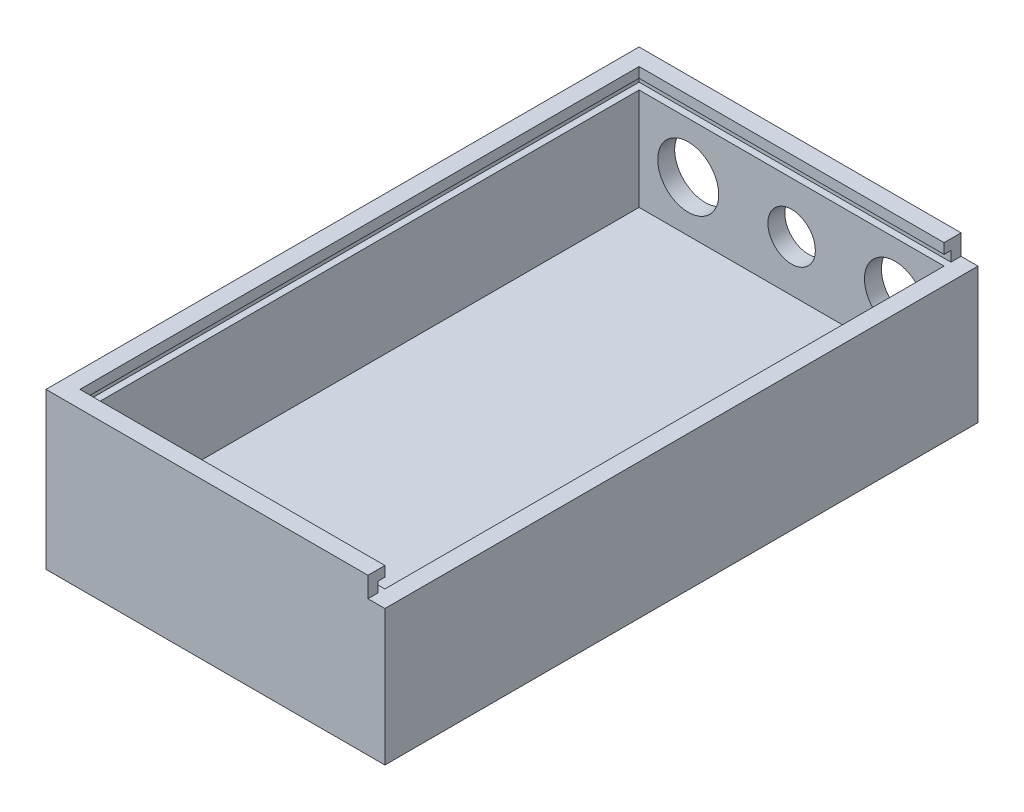
SolidWorks part; units mm, degrees
ref_plane "Front Plane" through (0, 0, 0) normal (0, 0, 1) x (1, 0, 0)
ref_plane "Top Plane" through (0, 0, 0) normal (0, 1, 0) x (1, 0, 0)
ref_plane "Right Plane" through (0, 0, 0) normal (1, 0, 0) x (0, 0, -1)
sketch "Sketch1" plane through (0, 0, 0) normal (0, 0, 1) x (1, 0, 0)
  line L0 (6.2525, 13.33) -> (6.2525, -26.67) construction
  line L1 (-43.7475, 13.33) -> (56.2525, 13.33)
  line L2 (-43.7475, 13.33) -> (-43.7475, -26.67)
  line L3 (-43.7475, -26.67) -> (56.2525, -26.67)
  line L4 (56.2525, 13.33) -> (56.2525, -26.67)
  line L5 (-43.7475, -6.67) -> (56.2525, -6.67) construction
  line L6 (6.2525, -6.67) -> (36.7525, -6.67)
  line L7 (6.2525, -6.67) -> (-24.2475, -6.67)
  circle A0 centre (6.2525, -6.67) radius 6.5
  circle A1 centre (36.7525, -6.67) radius 9
  circle A2 centre (-24.2475, -6.67) radius 9
  dimension "D3" = 13
  dimension "D5" = 18
  dimension "D7" = 18
  dimension "D1" = 100
  dimension "D2" = 40
  dimension "D4" = 30.5
  dimension "D6" = 30.5
extrude "Boss-Extrude1" add sketch "Sketch1" along normal blind 175 contours L2 L1 L4 L3
sketch "Sketch2" plane through (0, 13.33, 0) normal (0, 1, 0) x (1, 0, 0)
  line L0 (6.2525, 0) -> (6.2525, -175) construction
  line L2 (56.2525, -87.5) -> (-43.7475, -87.5) construction
  line L3 (56.2525, -175) -> (56.2525, 0) construction
  line L4 (-43.7475, -175) -> (-43.7475, 0) construction
  line L5 (-43.7475, 0) -> (56.2525, 0) construction
  line L10 (-43.7475, -175) -> (56.2525, -175) construction
  line L11 (-38.7475, -170) -> (51.2525, -170)
  line L12 (-38.7475, -170) -> (-38.7475, -5)
  line L13 (-38.7475, -5) -> (51.2525, -5)
  line L14 (51.2525, -170) -> (51.2525, -5)
  line L15 (-38.7475, -170) -> (51.2525, -5) construction
  line L16 (-38.7475, -5) -> (51.2525, -170) construction
  point P4 (6.2525, -87.5)
  dimension "D2" = 90
  dimension "D3" = 165
extrude "Cut-Extrude1" cut sketch "Sketch2" against normal blind 30 contours L12 L11 L14 L13
ref_plane "Plane1" through (0, 13.33, 0) normal (0, 1, 0) x (1, 0, 0)
ref_plane "Plane10" through (0, -16.67, 0) normal (0, 1, 0) x (1, 0, 0)
sketch "Sketch18" plane through (0, 0, 0) normal (0, 0, 1) x (1, 0, 0)
  line L0 (56.2525, 13.33) -> (56.2525, -26.67) construction
  line L1 (-43.7475, 13.33) -> (-43.7475, -26.67) construction
  line L2 (-43.7475, 13.33) -> (56.2525, 13.33) construction
  circle A0 centre (6.2525, -1.67) radius 7
  circle A2 centre (36.7525, -1.67) radius 9
  circle A3 centre (-24.2475, -1.67) radius 9
  dimension "D1" = 14
  dimension "D2" = 30.5
  dimension "D3" = 50
  dimension "D4" = 18
  dimension "D7" = 18
  dimension "D5" = 50
  dimension "D6" = 30.5
  dimension "D8" = 15
extrude "Cut-Extrude9" cut sketch "Sketch18" along normal blind 10
sketch "Sketch26" plane through (0, 13.33, 0) normal (0, 1, 0) x (1, 0, 0)
  line L0 (51.2525, -5) -> (-38.7475, -5)
  line L1 (-38.7475, -5) -> (-38.7475, -170)
  line L2 (-38.7475, -170) -> (51.2525, -170)
  line L3 (51.2525, -170) -> (51.2525, -175)
  line L4 (-43.7475, -175) -> (56.2525, -175) construction
  line L5 (51.2525, -175) -> (-43.7475, -175)
  line L6 (-43.7475, -175) -> (-43.7475, 0)
  line L7 (-43.7475, 0) -> (51.2525, 0)
  line L8 (-43.7475, 0) -> (56.2525, 0) construction
  line L9 (51.2525, 0) -> (51.2525, -5)
extrude "Boss-Extrude3" add sketch "Sketch26" along normal blind 6
sketch "Sketch27" plane through (51.2525, 0, 0) normal (1, 0, 0) x (0, 0, -1)
  line L0 (-170, 13.33) -> (-172, 13.33)
  line L1 (-175, 13.33) -> (-170, 13.33) construction
  line L2 (-170, 19.33) -> (-170, 13.33) construction
  line L4 (-172, 13.33) -> (-172, 16.33)
  line L5 (-172, 16.33) -> (-170, 16.33)
  line L6 (-170, 13.33) -> (-170, 16.33)
  dimension "D1" = 2
  dimension "D2" = 3
extrude "Cut-Extrude13" cut sketch "Sketch27" against normal blind 92
sketch "Sketch28" plane through (51.2525, 0, 0) normal (1, 0, 0) x (0, 0, -1)
  line L1 (-5, 13.33) -> (-3, 13.33)
  line L2 (-5, 13.33) -> (-5, 16.33)
  line L3 (-5, 16.33) -> (-3, 16.33)
  line L4 (-3, 13.33) -> (-3, 16.33)
  dimension "D1" = 2
  dimension "D2" = 3
extrude "Cut-Extrude14" cut sketch "Sketch28" against normal blind 92
sketch "Sketch29" plane through (-38.7475, 0, 0) normal (1, 0, 0) x (0, 0, -1)
  line L1 (-170, 16.33) -> (-5, 16.33)
  line L2 (-170, 16.33) -> (-170, 13.33)
  line L3 (-170, 13.33) -> (-5, 13.33)
  line L4 (-5, 16.33) -> (-5, 13.33)
extrude "Cut-Extrude15" cut sketch "Sketch29" against normal blind 2
